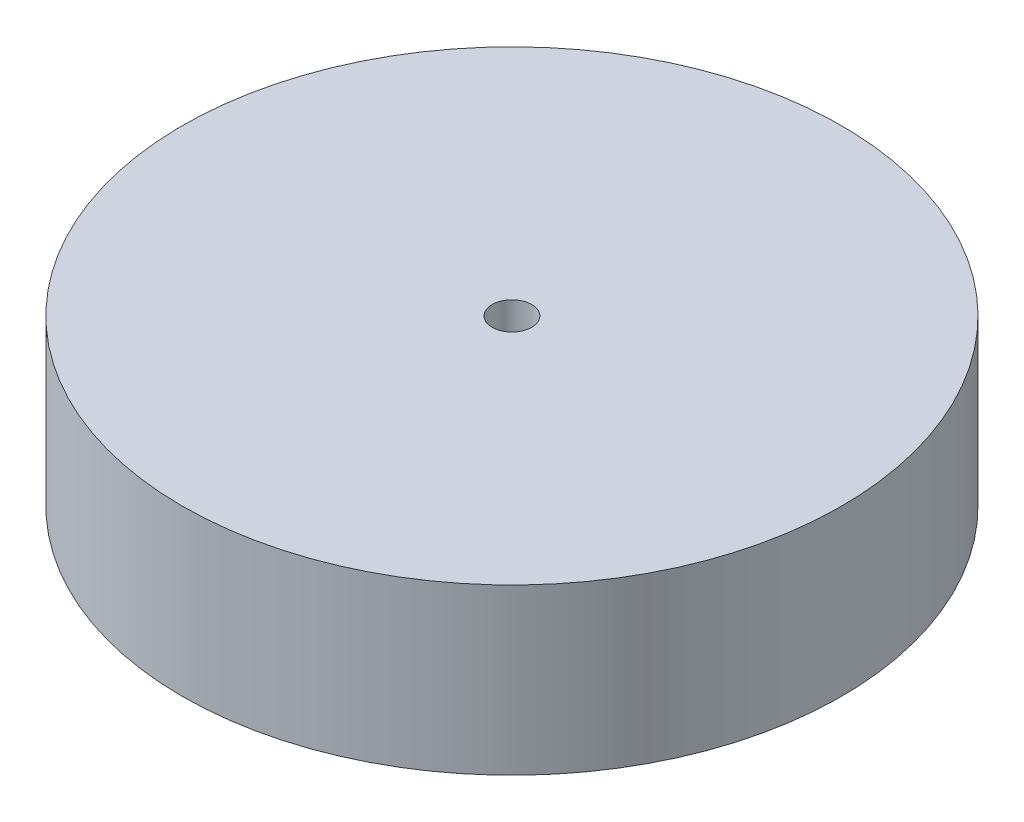
SolidWorks part; units mm, degrees
material "Rubber"
ref_plane "Front Plane" through (0, 0, 0) normal (0, 0, 1) x (1, 0, 0)
ref_plane "Top Plane" through (0, 0, 0) normal (0, 1, 0) x (1, 0, 0)
ref_plane "Right Plane" through (0, 0, 0) normal (1, 0, 0) x (0, 0, -1)
sketch "Sketch1" plane through (0, 0, 0) normal (0, 1, 0) x (1, 0, 0)
  circle A0 centre (0, 0) radius 3
  circle A1 centre (0, 0) radius 50
extrude "Boss-Extrude1" add sketch "Sketch1" along normal blind 25
